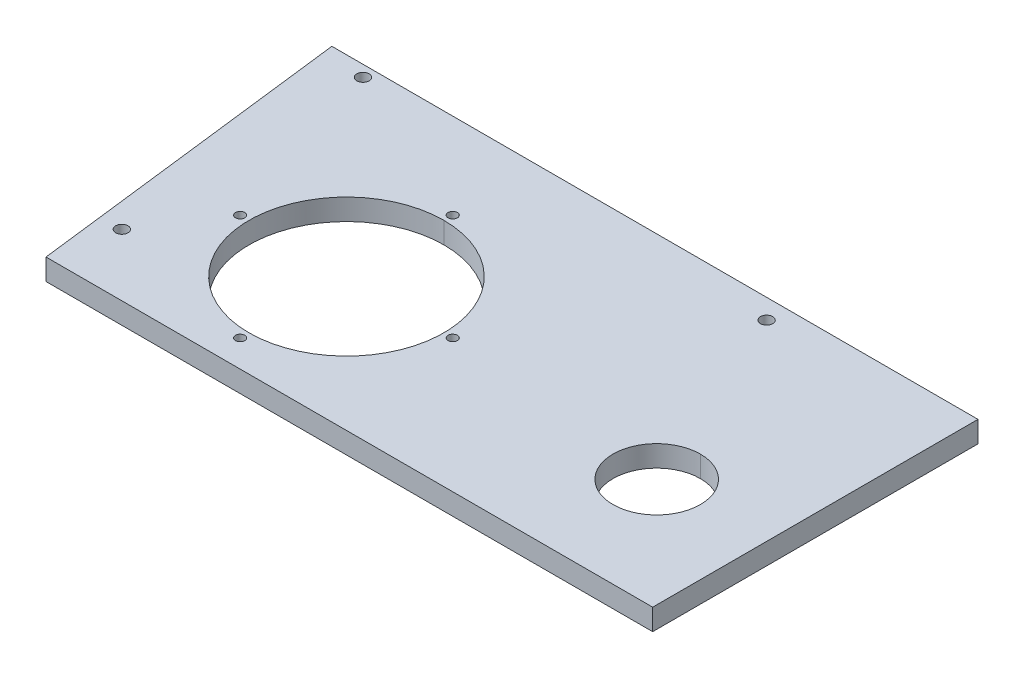
SolidWorks part; units mm, degrees
material "7075-T6 (SN)"
ref_plane "X-Y Datum" through (0, 0, 0) normal (0, 0, 1) x (1, 0, 0)
ref_plane "X-Z Datum" through (0, 0, 0) normal (0, 1, 0) x (1, 0, 0)
ref_plane "Y-Z Datum" through (0, 0, 0) normal (1, 0, 0) x (0, 0, -1)
sketch "Sketch1" plane through (0, 0, 0) normal (0, 1, 0) x (1, 0, 0)
  line L0 (-228.6, -165.1) -> (-123.19, -116.0015) construction
  line L1 (0, 0) -> (54.61, -127) construction
  line L2 (-123.19, -116.0015) -> (54.61, -127) construction
  line L3 (-228.6, -165.1) -> (-228.6, 0) construction
  line L4 (-116.84, 0) -> (0, 0) construction
  line L5 (-228.6, 0) -> (-116.84, 0) construction
  line L6 (-234.329, -12.7) -> (113.0614, -12.7)
  line L7 (113.0614, -12.7) -> (113.0614, -187.6049)
  line L8 (-234.329, -12.7) -> (-213.0648, -187.6587)
  line L9 (-213.0648, -187.6587) -> (113.0614, -187.6049)
  line L10 (-228.6, 0) -> (-123.19, -116.0015) construction
  line L11 (-123.19, -116.0015) -> (10.0337, -23.3342) construction
  circle A0 centre (-211.5182, -18.7982) radius 9.525 construction
  circle A1 centre (-205.5752, -154.3754) radius 9.525 construction
  circle A2 centre (10.0337, -23.3342) radius 9.525 construction
  circle A3 centre (-211.5182, -18.7982) radius 3.3 construction
  circle A4 centre (-205.5752, -154.3754) radius 3.3 construction
  circle A5 centre (-123.19, -116.0015) radius 52.3875
  circle A6 centre (54.61, -127) radius 23.5
  circle A7 centre (0, 0) radius 12.7 construction
  circle A8 centre (-228.6, -165.1) radius 12.7 construction
  circle A9 centre (-228.6, 0) radius 12.7 construction
  circle A10 centre (10.0337, -23.3342) radius 3.3 construction
  circle A11 centre (-123.19, -173.1515) radius 2.5 construction
  point P36 (-123.19, -116.0015)
  dimension "D1" = 165.1
  dimension "D2" = 105.41
  dimension "D8" = 25.4
  dimension "D9" = 104.775
  dimension "D10" = 47
  dimension "D11" = 19.05
  dimension "D12" = 6.6
  dimension "D23" = 5
  dimension "D3" = 111.76
  dimension "D4" = 228.6
  dimension "D5" = 127
  dimension "D6" = 49.0985
  dimension "D7" = 283.21
  dimension "D13" = 25.4
  dimension "D15" = 25.4
  dimension "D17" = 25.4
  dimension "D19" = 22.5587
  dimension "D20" = 15.5352
  dimension "D21" = 60.6049
  dimension "D22" = 58.4514
  dimension "D24" = 57.15
extrude "Boss-Extrude1" add sketch "Sketch1" along normal blind 11.43
hole_wizard "M6 Clearance Hole1" positions "Sketch2" profile "Sketch3" hole size "M6" standard "ANSI Metric" end condition through all
sketch "Sketch2" plane through (0, 0, 0) normal (0, -1, 0) x (-1, 0, 0)
  point P0 (-10.0337, -23.3342)
  point P3 (211.5182, -18.7982)
  point P6 (205.5752, -154.3754)
sketch "Sketch3" plane through (10.0337, 0, 23.3342) normal (1, 0, 0) x (0, 0, -1)
  line L0 (0, 0) -> (0, 11.43)
  line L1 (0, 11.43) -> (3.3, 11.43)
  line L2 (3.3, 11.43) -> (3.3, 0)
  line L5 (3.3, 0) -> (0, 0)
  line L11 (0, -6.35) -> (0, 107.95) construction
  dimension "Thru Hole Dia." = 6.6
  dimension "Thru Hole Depth" = 11.43
hole_wizard "Ø5.0mm Dowel Hole1" positions "Sketch4" profile "Sketch5" hole size "Ø5.0" standard "ANSI Metric" end condition through all
sketch "Sketch4" plane through (0, 0, 0) normal (0, -1, 0) x (-1, 0, 0)
  point P0 (123.19, -173.1515)
sketch "Sketch5" plane through (-123.19, 0, 173.1515) normal (1, 0, 0) x (0, 0, -1)
  line L0 (0, 0) -> (0, 11.43)
  line L1 (0, 11.43) -> (2.5, 11.43)
  line L2 (2.5, 11.43) -> (2.5, 0)
  line L5 (2.5, 0) -> (0, 0)
  line L11 (0, -6.35) -> (0, 107.95) construction
  dimension "Thru Hole Dia." = 5
  dimension "Thru Hole Depth" = 11.43
pattern_circular "CirPattern1" count 4 over 360 about axis through (-123.19, 0, 116.0015) along (0, 1, 0) of "Ø5.0mm Dowel Hole1"
ref_point "Point1"
ref_point "Point2"
ref_plane "Plane1" through (-123.19, 0, 0) normal (1, 0, 0) x (0, 0, -1)
ref_plane "Plane2" through (54.61, 0, 0) normal (1, 0, 0) x (0, 0, -1)
split line "Split Line1"
split line "Split Line2"
